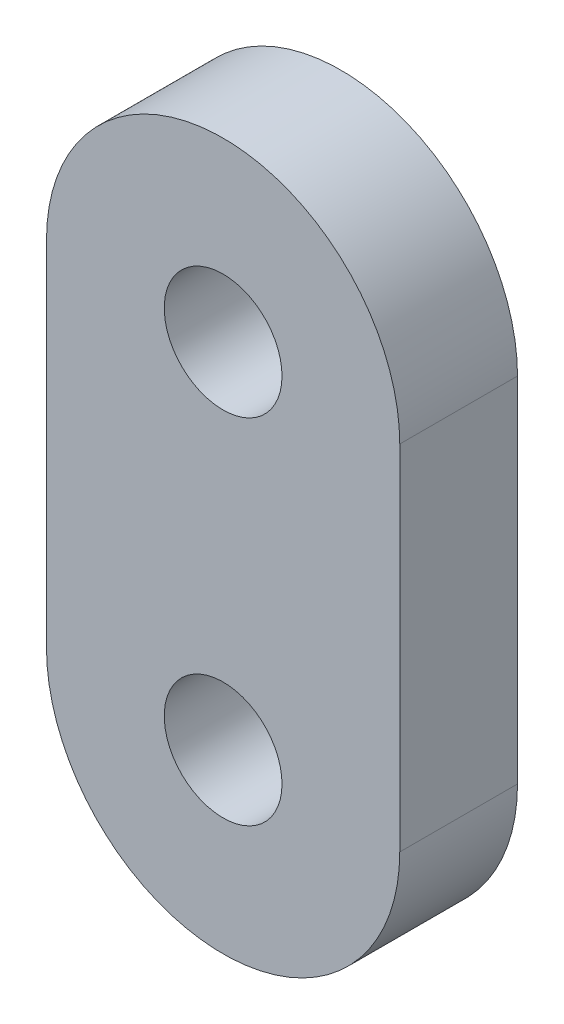
SolidWorks part; units mm, degrees
ref_plane "Alzado" through (0, 0, 0) normal (0, 0, 1) x (1, 0, 0)
ref_plane "Planta" through (0, 0, 0) normal (0, 1, 0) x (1, 0, 0)
ref_plane "Vista lateral" through (0, 0, 0) normal (1, 0, 0) x (0, 0, -1)
sketch "Model" plane through (0, 0, 0) normal (0, 0, 1) x (1, 0, 0)
  line L0 (213.2508, 152.4285) -> (213.2508, 161.4285)
  line L1 (204.2508, 161.4285) -> (204.2508, 152.4285)
  circle A0 centre (208.7508, 152.4285) radius 1.5
  circle A1 centre (208.7508, 161.4285) radius 1.5
  arc A2 (204.2508, 152.4285) -> (213.2508, 152.4285) centre (208.7508, 152.4285) ccw
  arc A3 (213.2508, 161.4285) -> (204.2508, 161.4285) centre (208.7508, 161.4285) ccw
extrude "Saliente-Extruir1" add sketch "Model" along normal blind 3
